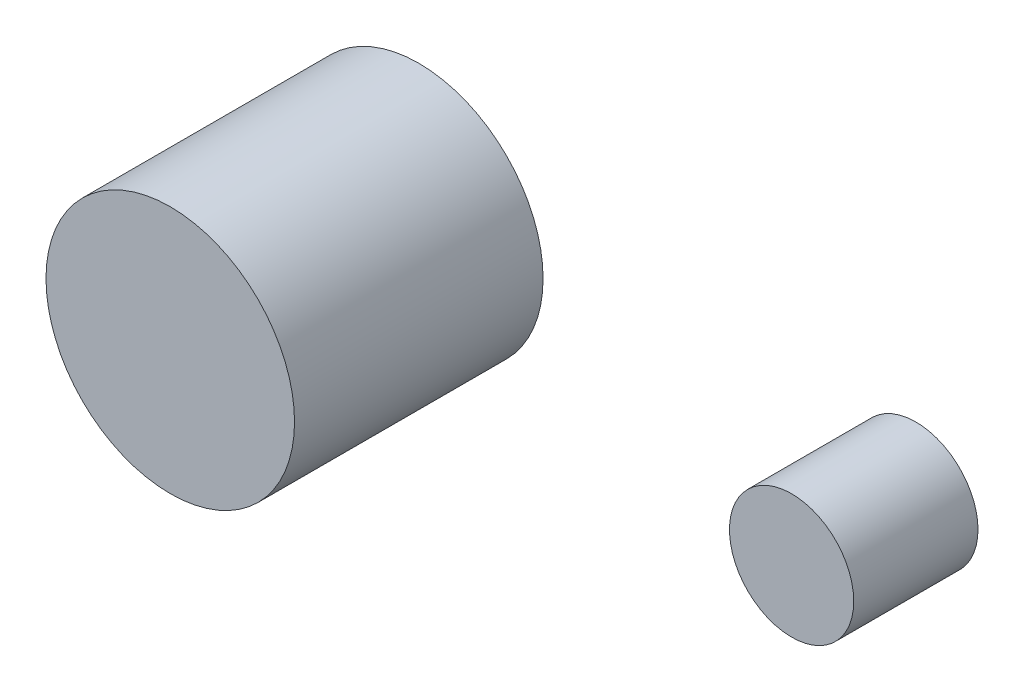
SolidWorks part; units mm, degrees
ref_plane "Front Plane" through (0, 0, 0) normal (0, 0, 1) x (1, 0, 0)
ref_plane "Top Plane" through (0, 0, 0) normal (0, 1, 0) x (1, 0, 0)
ref_plane "Right Plane" through (0, 0, 0) normal (1, 0, 0) x (0, 0, -1)
ref_plane "plane:xy" through (0, 0, 0) normal (0, 0, 1) x (1, 0, 0)
sketch "sketch:first" plane through (0, 0, 0) normal (0, 0, 1) x (1, 0, 0)
  circle A0 centre (0, 0) radius 10
extrude "feature:first" add sketch "sketch:first" along normal blind 20 separate body
sketch "sketch:second" plane through (0, 0, 0) normal (0, 0, 1) x (1, 0, 0)
  circle A0 centre (40, 0) radius 5
extrude "feature:second" add sketch "sketch:second" along normal blind 10 separate body
